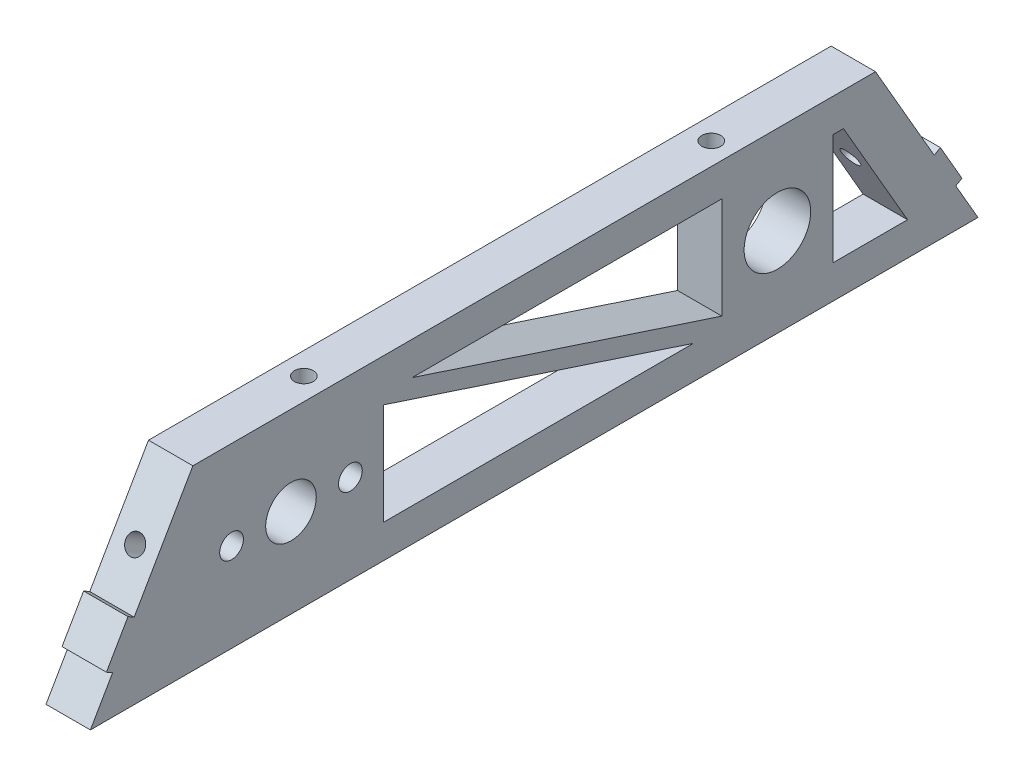
SolidWorks part; units mm, degrees
material "6061-T6 (SS)"
ref_plane "Front Plane" through (0, 0, 0) normal (0, 0, 1) x (1, 0, 0)
ref_plane "Top Plane" through (0, 0, 0) normal (0, 1, 0) x (1, 0, 0)
ref_plane "Right Plane" through (0, 0, 0) normal (1, 0, 0) x (0, 0, -1)
sketch "Sketch1" plane through (0, 0, 0) normal (1, 0, 0) x (0, 0, -1)
  line L0 (0, 0) -> (-14.6647, 25.4)
  line L1 (0, 0) -> (-127, 0)
  line L3 (-14.6647, 25.4) -> (-112.3353, 25.4)
  line L5 (-127, 0) -> (-112.3353, 25.4)
  circle A0 centre (-98.298, 12.7) radius 3.6195
  circle A1 centre (-28.702, 12.7) radius 4.7625
  circle A2 centre (-89.798, 12.7) radius 1.7
  circle A3 centre (-106.798, 12.7) radius 1.7
  dimension "D3" = 7.239
  dimension "D5" = 9.525
  dimension "D9" = 3.4
  dimension "D2" = 25.4
  dimension "D4" = 12.7
  dimension "D6" = 127
  dimension "D7" = 28.702
  dimension "D8" = 12.7
  dimension "D10" = 8.5
  dimension "D11" = 8.5
  dimension "D13" = 60
  dimension "D14" = 60
  dimension "D15" = 28.702
extrude "Boss-Extrude1" add sketch "Sketch1" along normal blind 6.35
hole_wizard "Tap Drill for #6-32 Tap4" positions "Sketch7" profile "Sketch6" hole size "#6-32" standard "ANSI Inch"
sketch "Sketch7" plane through (0, 25.4, 0) normal (0, 1, 0) x (1, 0, 0)
  line L2 (0, -14.6647) -> (0, -112.3353) construction
  line L4 (6.35, -14.6647) -> (6.35, -112.3353) construction
  line L7 (6.35, -14.6647) -> (0, -14.6647) construction
  line L8 (6.35, -112.3353) -> (0, -112.3353) construction
  point P0 (3.175, -93.2853)
  point P2 (3.175, -34.9847)
  point P16 (3.175, -34.9847)
  point P18 (3.175, -93.2853)
  point P22 (3.175, -93.2853)
  dimension "D1" = 19.05
  dimension "D2" = 20.32
  dimension "D3" = 3.175
  dimension "D4" = 3.175
sketch "Sketch6" plane through (3.175, 25.4, 93.2853) normal (1, 0, 0) x (0, 0, 1)
  line L0 (0, 0) -> (0, 10.9727)
  line L1 (0, 10.9727) -> (1.3525, 10.16)
  line L2 (1.3525, 10.16) -> (1.3525, 0)
  line L5 (1.3525, 0) -> (0, 0)
  line L10 (0, 10.9727) -> (-1.3526, 10.16) construction
  line L11 (0, -6.35) -> (0, 107.95) construction
  dimension "Hole Dia." = 2.7051
  dimension "Hole Depth" = 10.16
  dimension "Drill Angle" = 118
hole_wizard "Tap Drill for #6-32 Tap3" positions "Sketch9" profile "Sketch8" hole size "#6-32" standard "ANSI Inch"
sketch "Sketch9" plane through (0, 0, 0) normal (0, -1, 0) x (-1, 0, 0)
  line L1 (0, -127) -> (0, 0) construction
  line L3 (-6.35, 0) -> (0, 0) construction
  line L4 (-6.35, -127) -> (0, -127) construction
  point P0 (-3.175, -92.71)
  point P2 (-3.175, -22.86)
  dimension "D1" = 22.86
  dimension "D2" = 3.175
  dimension "D3" = 34.29
  dimension "D4" = 3.175
sketch "Sketch8" plane through (3.175, 0, 92.71) normal (1, 0, 0) x (0, 0, -1)
  line L0 (0, 0) -> (0, 10.9727)
  line L1 (0, 10.9727) -> (1.3525, 10.16)
  line L2 (1.3525, 10.16) -> (1.3525, 0)
  line L5 (1.3525, 0) -> (0, 0)
  line L10 (0, 10.9727) -> (-1.3526, 10.16) construction
  line L11 (0, -6.35) -> (0, 107.95) construction
  dimension "Hole Dia." = 2.7051
  dimension "Hole Depth" = 10.16
  dimension "Drill Angle" = 118
sketch "Sketch11" plane through (0, 54.9926, 95.25) normal (0, 0.5, 0.866) x (1, 0, 0)
  line L0 (0, -34.1706) -> (0, -63.5) construction
  line L1 (0, -50.9778) -> (6.35, -50.9778)
  line L2 (0, -50.9778) -> (0, -57.15)
  line L3 (0, -57.15) -> (6.35, -57.15)
  line L4 (6.35, -50.9778) -> (6.35, -57.15)
  line L5 (6.35, -34.1706) -> (6.35, -63.5) construction
  line L6 (6.35, -63.5) -> (0, -63.5) construction
  dimension "D1" = 6.1722
  dimension "D2" = 6.35
extrude "Boss-Extrude2" add sketch "Sketch11" along normal blind 1.016
sketch "Sketch12" plane through (0, 0, 0) normal (0, 0.5, -0.866) x (-1, 0, 0)
  line L0 (-6.35, 0) -> (-6.35, 29.3294) construction
  line L1 (-6.35, 12.5222) -> (0, 12.5222)
  line L2 (-6.35, 12.5222) -> (-6.35, 6.35)
  line L3 (-6.35, 6.35) -> (0, 6.35)
  line L4 (0, 12.5222) -> (0, 6.35)
  line L5 (0, 0) -> (0, 29.3294) construction
  line L6 (-6.35, 0) -> (0, 0) construction
  dimension "D1" = 6.1722
  dimension "D2" = 6.35
extrude "Boss-Extrude3" add sketch "Sketch12" along normal blind 1.016
hole_wizard "Tap Drill for #6-32 Tap1" positions "Sketch14" profile "Sketch13" hole size "#6-32" standard "ANSI Inch"
sketch "Sketch14" plane through (0, 54.9926, 95.25) normal (0, 0.5, 0.866) x (1, 0, 0)
  line L0 (6.35, -34.1706) -> (6.35, -50.9778) construction
  line L1 (6.35, -34.1706) -> (0, -34.1706) construction
  point P0 (3.175, -44.3306)
  dimension "D1" = 3.175
  dimension "D2" = 10.16
sketch "Sketch13" plane through (3.175, 16.6012, 117.4153) normal (1, 0, 0) x (0, -0.866, 0.5)
  line L0 (0, 0) -> (0, 8.4327)
  line L1 (0, 8.4327) -> (1.3525, 7.62)
  line L2 (1.3525, 7.62) -> (1.3525, 0)
  line L5 (1.3525, 0) -> (0, 0)
  line L10 (0, 8.4327) -> (-1.3526, 7.62) construction
  line L11 (0, -6.35) -> (0, 107.95) construction
  dimension "Hole Dia." = 2.7051
  dimension "Hole Depth" = 7.62
  dimension "Drill Angle" = 118
hole_wizard "Tap Drill for #6-32 Tap2" positions "Sketch16" profile "Sketch15" hole size "#6-32" standard "ANSI Inch"
sketch "Sketch16" plane through (0, 0, 0) normal (0, 0.5, -0.866) x (-1, 0, 0)
  line L0 (0, 12.5222) -> (0, 29.3294) construction
  line L1 (-6.35, 29.3294) -> (0, 29.3294) construction
  point P0 (-3.175, 19.1694)
  dimension "D1" = 3.175
  dimension "D2" = 10.16
sketch "Sketch15" plane through (3.175, 16.6012, 9.5847) normal (1, 0, 0) x (0, 0.866, 0.5)
  line L0 (0, 0) -> (0, 8.4327)
  line L1 (0, 8.4327) -> (1.3525, 7.62)
  line L2 (1.3525, 7.62) -> (1.3525, 0)
  line L5 (1.3525, 0) -> (0, 0)
  line L10 (0, 8.4327) -> (-1.3525, 7.62) construction
  line L11 (0, -6.35) -> (0, 107.95) construction
  dimension "Hole Dia." = 2.7051
  dimension "Hole Depth" = 7.62
  dimension "Drill Angle" = 118
sketch "Sketch19" plane through (0, 0, 0) normal (-1, 0, 0) x (0, 0, 1)
  line L0 (14.6647, 25.4) -> (112.3353, 25.4) construction
  line L1 (36.6395, 20.6375) -> (85.0355, 20.6375)
  line L2 (36.6395, 20.6375) -> (36.6395, 4.7625)
  line L3 (36.6395, 4.7625) -> (85.0355, 4.7625)
  line L4 (85.0355, 20.6375) -> (85.0355, 4.7625)
  line L5 (127, 0) -> (0, 0) construction
  line L6 (36.6395, 4.7625) -> (85.0355, 20.6375) construction
  line L7 (40.7142, 4.7625) -> (85.0355, 19.3009)
  line L8 (36.6395, 6.0991) -> (80.9608, 20.6375)
  line L9 (36.2437, 5.9692) -> (84.6397, 21.8442) construction
  line L10 (37.0353, 3.5558) -> (85.4313, 19.4308) construction
  line L11 (10.082, 4.7625) -> (19.2474, 20.6375)
  line L12 (20.7645, 20.6375) -> (20.7645, 4.7625)
  line L13 (20.7645, 4.7625) -> (10.082, 4.7625)
  line L14 (6.2611, 10.8445) -> (14.6647, 25.4) construction
  line L15 (20.7645, 20.6375) -> (19.2474, 20.6375)
  circle A0 centre (28.702, 12.7) radius 4.7625 construction
  circle A1 centre (89.798, 12.7) radius 1.7 construction
  dimension "D1" = 4.7625
  dimension "D2" = 4.7625
  dimension "D3" = 7.9375
  dimension "D4" = 4.7625
  dimension "D7" = 6.35
  dimension "D8" = 7.9375
  dimension "D9" = 4.7625
  dimension "D5" = 1.27
  dimension "D6" = 1.27
extrude "Cut-Extrude1" cut sketch "Sketch19" against normal through all contours L2 L8 L1 | L7 L3 L4 | L12 L15 L11 L13
equation "\"D8@Sketch1\"=\"D4@Sketch1\""
equation "\"D11@Sketch1\"=\"D10@Sketch1\""
